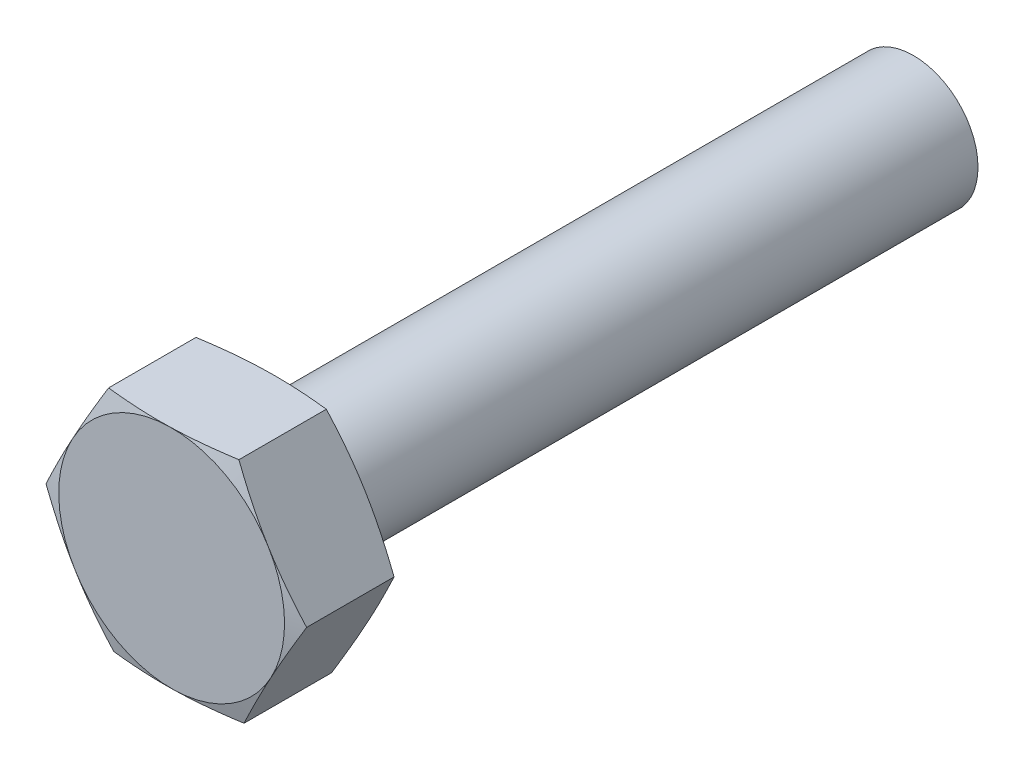
SolidWorks part; units mm, degrees
ref_plane "Plano frontal" through (0, 0, 0) normal (0, 0, 1) x (1, 0, 0)
ref_plane "Plano superior" through (0, 0, 0) normal (0, 1, 0) x (1, 0, 0)
ref_plane "Plano direito" through (0, 0, 0) normal (1, 0, 0) x (0, 0, -1)
sketch "Esboço1" plane through (0, 0, 0) normal (0, 0, 1) x (1, 0, 0)
  line L1 (3.881, 7.0902) -> (-4.1998, 6.9062)
  line L2 (-4.1998, 6.9062) -> (-8.0808, -0.1841)
  line L3 (-8.0808, -0.1841) -> (-3.881, -7.0902)
  line L4 (-3.881, -7.0902) -> (4.1998, -6.9062)
  line L5 (4.1998, -6.9062) -> (8.0808, 0.1841)
  line L6 (8.0808, 0.1841) -> (3.881, 7.0902)
  circle A0 centre (0, 0) radius 7 construction
  dimension "D1" = 14
extrude "Ressalto-extrusão1" add sketch "Esboço1" along normal blind 6
sketch "Esboço2" plane through (0, 0, 6) normal (0, 0, 1) x (1, 0, 0)
  circle A0 centre (0, 0) radius 7
extrude "Corte-extrusão1" cut sketch "Esboço2" against normal blind 13 draft 75 flip side to cut
sketch "Esboço9" plane through (0, 0, 0) normal (0, 0, -1) x (-1, 0, 0)
  circle A0 centre (0, 0) radius 7
extrude "Corte-extrusão6" cut sketch "Esboço9" against normal blind 13 draft 75 flip side to cut
sketch "Esboço10" plane through (0, 0, 0) normal (0, 0, -1) x (-1, 0, 0)
  circle A0 centre (0, 0) radius 4
  dimension "D1" = 8
extrude "Ressalto-extrusão2" add sketch "Esboço10" along normal blind 40
cosmetic thread "Representação de rosca1" parameters "D1"=30, "D2"=6.619
